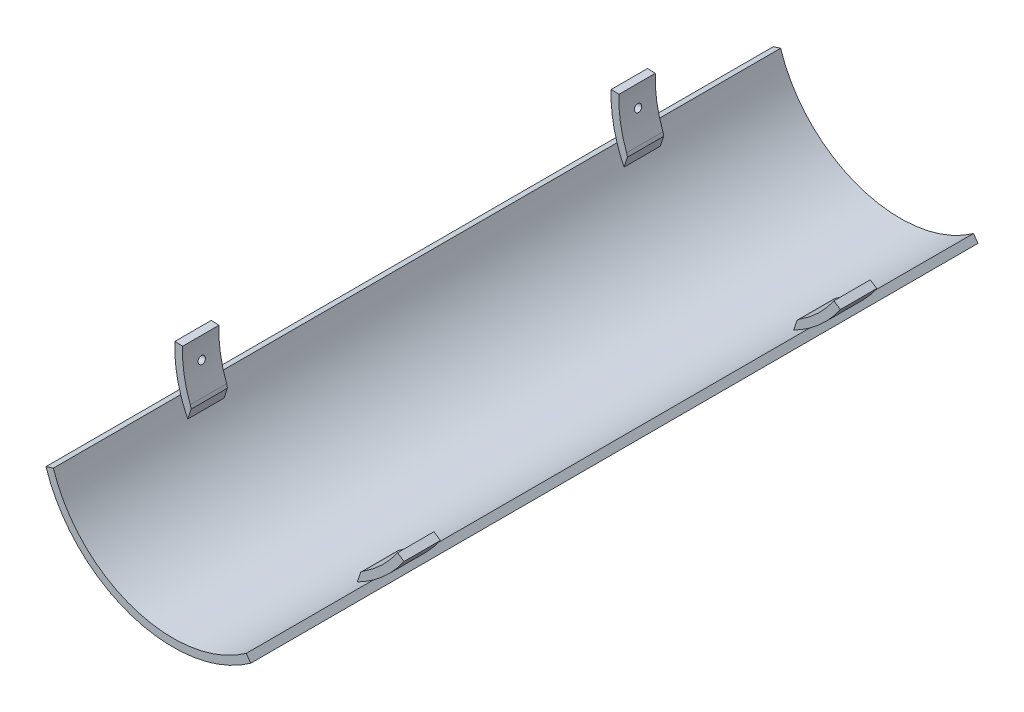
SolidWorks part; units mm, degrees
ref_plane "前视基准面" through (0, 0, 0) normal (0, 0, 1) x (1, 0, 0)
ref_plane "上视基准面" through (0, 0, 0) normal (0, 1, 0) x (1, 0, 0)
ref_plane "右视基准面" through (0, 0, 0) normal (1, 0, 0) x (0, 0, -1)
other "Configuration Table"
sketch "草图1" plane through (0, 0, 0) normal (0, 0, 1) x (1, 0, 0)
  line L0 (0, 0) -> (-52.4132, -16.6691) construction
  line L1 (0, 0) -> (32.0498, -44.6969) construction
  line L2 (-52.4132, -16.6691) -> (-49.3637, -15.6993)
  line L3 (30.1851, -42.0963) -> (32.0498, -44.6969)
  arc A0 (-49.3637, -15.6993) -> (30.1851, -42.0963) centre (0, 0) ccw
  arc A1 (-52.4132, -16.6691) -> (32.0498, -44.6969) centre (0, 0) ccw
  dimension "D1" = 110
  dimension "D2" = 103.6
  dimension "D3" = 108
extrude "凸台-拉伸1" add sketch "草图1" along normal mid plane 300
sketch "草图2" plane through (0, 0, -150) normal (0, 0, -1) x (-1, 0, 0)
  line L0 (0, 0) -> (-30.1851, -42.0963) construction
  line L1 (0, 0) -> (17.3221, -52.201) construction
  line L2 (-24.924, -42.0029) -> (-23.5075, -46.1588)
  line L3 (-40.1208, -27.4277) -> (-42.7625, -29.2337)
  line L4 (48.5589, 1.9992) -> (51.7562, 2.1309)
  line L5 (45.0905, -18.7697) -> (46.4395, -22.948)
  line L6 (0, 0) -> (-34.7485, -33.978) construction
  arc A1 (-40.1208, -27.4277) -> (-26.0428, -41.0333) centre (0, 0) ccw
  arc A2 (-32.0498, -44.6969) -> (52.4132, -16.6691) centre (0, 0) ccw construction
  arc A3 (-24.924, -42.0029) -> (-26.0428, -41.0333) centre (-28.7221, -45.2549) ccw
  arc A4 (-42.7625, -29.2337) -> (-23.5075, -46.1588) centre (0, 0) ccw
  arc A5 (51.7562, 2.1309) -> (46.4395, -22.948) centre (0, 0) cw
  arc A6 (45.0905, -18.7697) -> (45.4076, -17.3236) centre (50.0792, -19.1059) cw
  arc A7 (48.5589, 1.9992) -> (45.4076, -17.3236) centre (0, 0) cw
  dimension "D1" = 97.2
  dimension "D4" = 5
  dimension "D5" = 10
  dimension "D2" = 54
  dimension "D3" = 20
extrude "凸台-拉伸2" add sketch "草图2" against normal blind 247.5
sketch "草图3" plane through (0, 0, -150) normal (0, 0, -1) x (-1, 0, 0)
  circle A0 centre (0, 0) radius 51.8
extrude "切除-拉伸1" cut sketch "草图3" against normal blind 52.5
sketch "草图4" plane through (0, 0, 0) normal (0, 0, 1) x (1, 0, 0)
  circle A0 centre (0, 0) radius 51.8
extrude "切除-拉伸2" cut sketch "草图4" along normal mid plane 165
sketch "草图5" plane through (0, 0, -150) normal (0, 0, -1) x (-1, 0, 0)
  line L0 (0, 0) -> (-32.0498, -44.6969)
  line L1 (0, 0) -> (-37.0365, -36.2152)
  line L2 (0, 0) -> (30.9591, -31.6612)
  line L3 (0, 0) -> (52.4132, -16.6691)
  line L4 (0, 0) -> (55.6923, -7.4729)
  line L5 (0, 0) -> (-5.7306, -42.7077)
  arc A0 (-42.7625, -29.2337) -> (-30.1851, -42.0963) centre (0, 0) ccw construction
  dimension "D1" = 10
  dimension "D2" = 10
ref_plane "基准面1" through (0, 0, 0) normal (0.715, -0.6991, 0) x (-0.6991, -0.715, 0)
sketch "草图6" plane through (0, 0, 0) normal (0.715, -0.6991, 0) x (-0.6991, -0.715, 0)
  line L0 (0, 150) -> (0, -164.5168) construction
  circle A0 centre (0, 90) radius 1.5
  circle A1 centre (0, -90) radius 1.5
  dimension "D1" = 3
  dimension "D2" = 3
  dimension "D3" = 60
  dimension "D4" = 240
extrude "切除-拉伸3" cut sketch "草图6" along normal blind 165
ref_plane "基准面3" through (0, 0, 0) normal (0.9911, 0.133, 0) x (0.133, -0.9911, 0)
sketch "草图7" plane through (0, 0, 0) normal (0.9911, 0.133, 0) x (0.133, -0.9911, 0)
  line L0 (0, 150) -> (0, -135.6873) construction
  circle A0 centre (0, 90) radius 1.5
  circle A1 centre (0, -90) radius 1.5
  dimension "D3" = 3
  dimension "D4" = 3
  dimension "D1" = 60
  dimension "D2" = 240
extrude "切除-拉伸4" cut sketch "草图7" against normal blind 165
